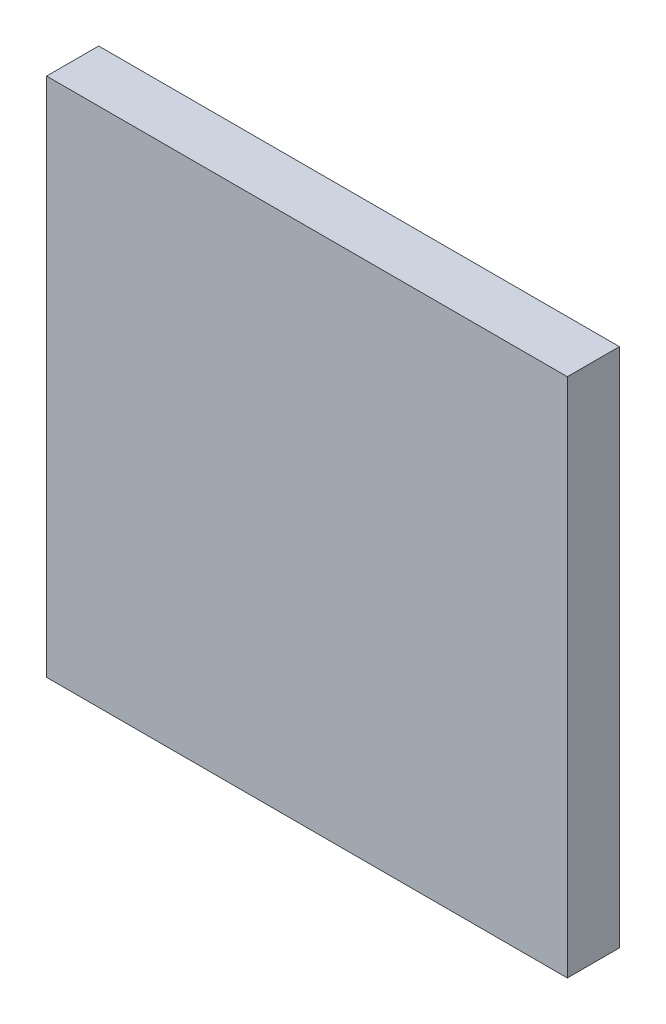
SolidWorks part; units mm, degrees
ref_plane "Alzado" through (0, 0, 0) normal (0, 0, 1) x (1, 0, 0)
ref_plane "Planta" through (0, 0, 0) normal (0, 1, 0) x (1, 0, 0)
ref_plane "Vista lateral" through (0, 0, 0) normal (1, 0, 0) x (0, 0, -1)
sketch "Croquis1" plane through (0, 0, 0) normal (0, 0, 1) x (1, 0, 0)
  line L1 (-5, -5) -> (5, -5)
  line L2 (-5, -5) -> (-5, 5)
  line L3 (-5, 5) -> (5, 5)
  line L4 (5, -5) -> (5, 5)
  line L5 (-5, -5) -> (5, 5) construction
  line L6 (-5, 5) -> (5, -5) construction
  point P0 (0, 0)
  dimension "D1" = 10
  dimension "D2" = 10
extrude "Saliente-Extruir1" add sketch "Croquis1" along normal blind 1
